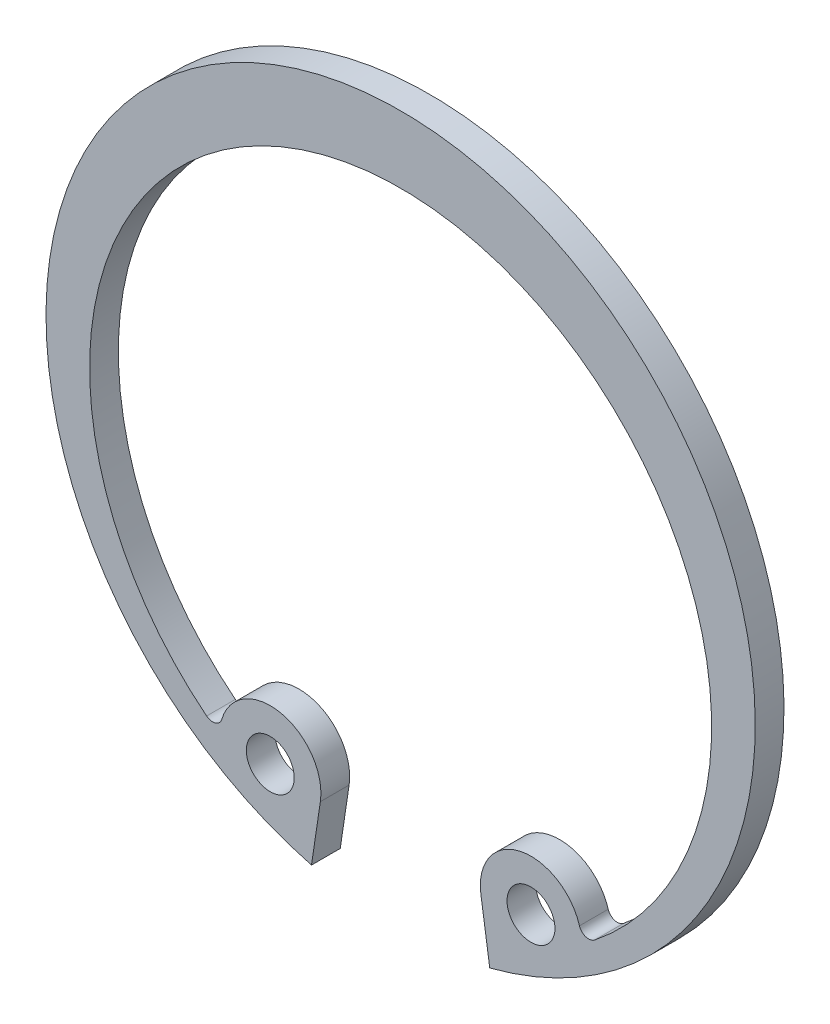
SolidWorks part; units mm, degrees
ref_plane "Front Plane" through (0, 0, 0) normal (0, 0, 1) x (1, 0, 0)
ref_plane "Top Plane" through (0, 0, 0) normal (0, 1, 0) x (1, 0, 0)
ref_plane "Right Plane" through (0, 0, 0) normal (1, 0, 0) x (0, 0, -1)
sketch "Sketch1" plane through (0, 0, 0) normal (0, 0, 1) x (1, 0, 0)
  line L0 (0, 0) -> (0, 18.5) construction
  line L1 (-4.1872, -14.8093) -> (-4.65, -17.9061)
  line L2 (4.1872, -14.8093) -> (4.65, -17.9061)
  line L3 (5.6731, -12.0294) -> (7.8912, -16.7326) construction
  arc A0 (4.65, -17.9061) -> (-4.65, -17.9061) centre (0, 0) ccw
  arc A1 (-10.1211, -13.9063) -> (-9.3303, -13.6592) centre (-9.8092, -13.5155) ccw
  circle A2 centre (-6.8, -14.4188) radius 1.25
  circle A3 centre (6.8, -14.4188) radius 1.25
  circle A4 centre (0, 0) radius 12 construction
  arc A6 (-4.1872, -14.8093) -> (-9.3303, -13.6592) centre (-6.8, -14.4188) ccw
  arc A7 (9.3303, -13.6592) -> (4.1872, -14.8093) centre (6.8, -14.4188) ccw
  arc A8 (10.1211, -13.9063) -> (-10.1211, -13.9063) centre (0, -1.225) ccw
  arc A9 (10.1211, -13.9063) -> (9.3303, -13.6592) centre (9.8092, -13.5155) cw
  point P13 (0, 15)
  dimension "D1" = 0.5
  dimension "RIC_D2_s" = 37
  dimension "D2" = 17
  dimension "RIC_D4_s" = 32.45
  dimension "RIC_D0_s" = 2.5
  dimension "RIC_D5_s" = 24
  dimension "RIC_B_s" = 3.5
  dimension "RIC_MSM_2" = 13.6
  dimension "RIC_MSM_1" = 9.3
  dimension "RIC_A_s" = 5.2
extrude "Boss-Extrude1" add sketch "Sketch1" along normal blind 1.5
equation "\"RIC_D4_s@Sketch1\"=\"RIC_D2_s@Sketch1\"-1.3*\"RIC_B_s@Sketch1\""
